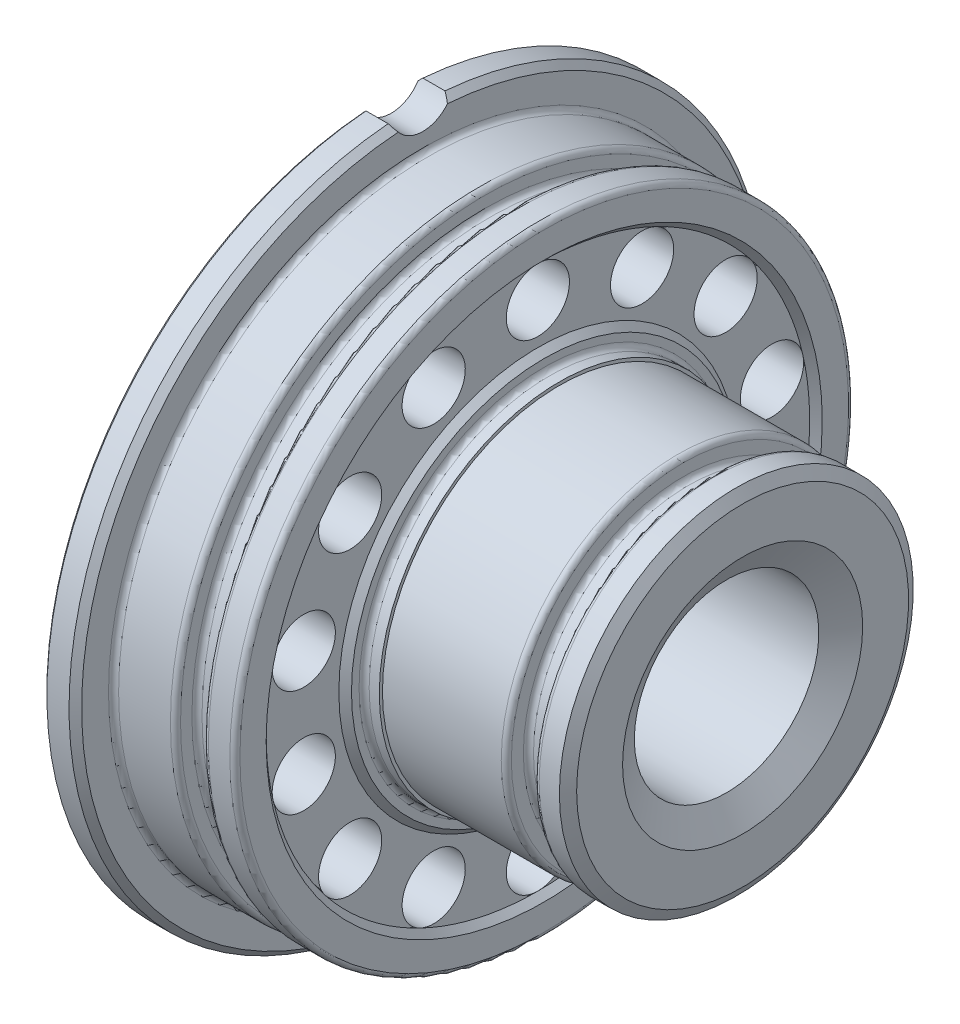
SolidWorks part; units mm, degrees
material "EN36A"
ref_plane "Front Plane" through (0, 0, 0) normal (0, 0, 1) x (1, 0, 0)
ref_plane "Top Plane" through (0, 0, 0) normal (0, 1, 0) x (1, 0, 0)
ref_plane "Right Plane" through (0, 0, 0) normal (1, 0, 0) x (0, 0, -1)
sketch "Sketch1" plane through (0, 0, 0) normal (0, 0, 1) x (1, 0, 0)
  line L0 (0, 0) -> (33.2077, 0) construction
  line L1 (0.4, 7.3) -> (26.5298, 7.3)
  line L2 (0.4, 7.3) -> (0.4, 13.5)
  line L4 (0, 13.9) -> (0, 27.25)
  line L5 (0.25, 27.5) -> (2, 27.5)
  line L6 (2.5, 27) -> (2.5, 24.875)
  line L7 (2.9, 24.475) -> (7, 24.475)
  line L8 (7.4, 24.075) -> (7.4, 23.175)
  line L9 (7.8, 22.775) -> (9.2, 22.775)
  line L10 (9.6, 23.175) -> (9.6, 24.075)
  line L11 (10, 24.475) -> (11.7, 24.475)
  line L12 (12.1, 24.075) -> (12.1, 22)
  line L13 (13.3, 14) -> (22.7, 14)
  line L14 (23.1, 12.65) -> (23.1, 13.6)
  line L15 (23.5, 12.25) -> (24.9, 12.25)
  line L16 (25.3, 12.65) -> (25.3, 13.6)
  line L17 (25.7, 14) -> (27.3, 14)
  line L18 (27.8, 13.134) -> (27.8, 9.5)
  line L19 (0.4, 13.5) -> (0, 13.9)
  line L21 (12.1, 15.25) -> (12.1, 14.65)
  line L22 (12.1, 15.25) -> (11.6, 15.75)
  line L23 (11.6, 21.5) -> (11.6, 15.75)
  line L24 (12.1, 22) -> (11.6, 21.5)
  line L25 (2, 27.5) -> (2.5, 27)
  line L26 (0, 27.25) -> (0.25, 27.5)
  line L27 (27.8, 9.5) -> (26.5298, 7.3)
  line L28 (27.3, 14) -> (27.8, 13.134)
  line L29 (12.5, 14.25) -> (13.3, 14.25)
  line L30 (13.3, 14.25) -> (13.3, 14)
  arc A0 (12.1, 14.65) -> (12.5, 14.25) centre (12.5, 14.65) ccw
  arc A1 (7.4, 23.175) -> (7.8, 22.775) centre (7.8, 23.175) ccw
  arc A2 (9.2, 22.775) -> (9.6, 23.175) centre (9.2, 23.175) ccw
  arc A3 (23.1, 12.65) -> (23.5, 12.25) centre (23.5, 12.65) ccw
  arc A4 (24.9, 12.25) -> (25.3, 12.65) centre (24.9, 12.65) ccw
  arc A6 (2.5, 24.875) -> (2.9, 24.475) centre (2.9, 24.875) ccw
  arc A7 (11.7, 24.475) -> (12.1, 24.075) centre (11.7, 24.075) cw
  arc A8 (7, 24.475) -> (7.4, 24.075) centre (7, 24.075) cw
  arc A9 (9.6, 24.075) -> (10, 24.475) centre (10, 24.075) cw
  arc A10 (22.7, 14) -> (23.1, 13.6) centre (22.7, 13.6) cw
  arc A11 (25.3, 13.6) -> (25.7, 14) centre (25.7, 13.6) cw
  point P33 (7.4, 22.775)
  point P36 (9.6, 22.775)
  point P39 (23.1, 12.25)
  point P42 (25.3, 12.25)
  point P48 (12.1, 24.475)
  point P53 (9.6, 24.475)
  point P58 (25.3, 14)
  dimension "D28" = 30.5
  dimension "D30" = 0.4
  dimension "D31" = 45
  dimension "D32" = 0.4
  dimension "D17" = 0.4
  dimension "D36" = 0.4
  dimension "D37" = 0.4
  dimension "D1" = 14.6
  dimension "D2" = 27
  dimension "D3" = 0.4
  dimension "D4" = 45
  dimension "D5" = 55
  dimension "D6" = 0.25
  dimension "D7" = 48.95
  dimension "D8" = 2.2
  dimension "D9" = 2.2
  dimension "D10" = 12.1
  dimension "D11" = 45.55
  dimension "D12" = 2.5
  dimension "D13" = 28
  dimension "D14" = 0.5
  dimension "D15" = 44
  dimension "D16" = 28.5
  dimension "D18" = 24.5
  dimension "D19" = 2.5
  dimension "D20" = 27.8
  dimension "D22" = 45
  dimension "D23" = 2.5
  dimension "D24" = 60
  dimension "D25" = 0.5
  dimension "D26" = 19
  dimension "D27" = 30
  dimension "D29" = 45
  dimension "D33" = 45
  dimension "D34" = 14.5
  dimension "D35" = 0.5
revolve "Revolve1" add sketch "Sketch1" angle 360 about L0
sketch "Sketch2" plane through (0, 0, 0) normal (-1, 0, 0) x (0, 0, 1)
  line L0 (0, 0) -> (37.309, 0) construction
  line L1 (0, 0) -> (0, 29.0181) construction
  circle A0 centre (0, 19) radius 2.5
  circle A1 centre (0, -19) radius 2.5
  dimension "D1" = 5
  dimension "D2" = 38
extrude "Extrude1" cut sketch "Sketch2" against normal up to next
sketch "Sketch3" plane through (0, 0, 0) normal (-1, 0, 0) x (0, 0, 1)
  line L0 (0, 0) -> (0, 32.8515) construction
  circle A0 centre (0, 28.5) radius 2.5
  circle A2 centre (0, 0) radius 27.5 construction
  circle A4 centre (0, 0) radius 27.5 construction
  dimension "D2" = 5
  dimension "D1" = 28.5
extrude "Extrude2" cut sketch "Sketch3" against normal up to next
pattern_circular "CirPattern1" count 7 over 360 about axis through (0, 0, 0) along (1, 0, 0) of "Extrude1"
